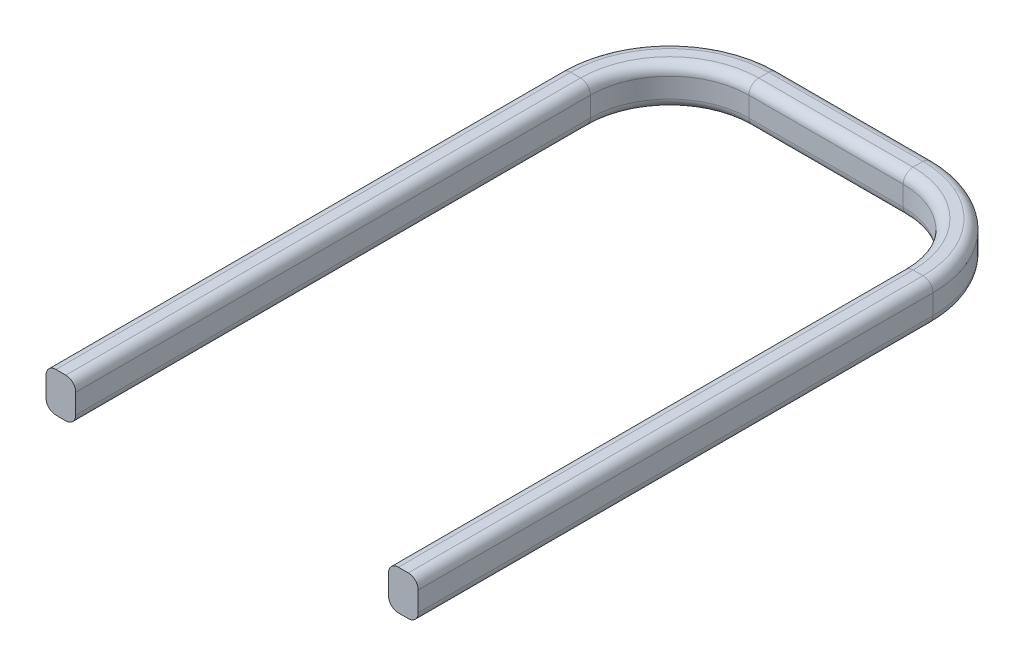
SolidWorks part; units mm, degrees
ref_plane "Front Plane" through (0, 0, 0) normal (0, 0, 1) x (1, 0, 0)
ref_plane "Top Plane" through (0, 0, 0) normal (0, 1, 0) x (1, 0, 0)
ref_plane "Right Plane" through (0, 0, 0) normal (1, 0, 0) x (0, 0, -1)
sketch "Sketch1" plane through (0, 0, 0) normal (0, 1, 0) x (1, 0, 0)
  line L0 (-3.95, 0) -> (-3.95, 13)
  line L1 (-1.95, 15) -> (1.95, 15)
  line L2 (3.95, 13) -> (3.95, 0)
  arc A0 (1.95, 15) -> (3.95, 13) centre (1.95, 13) cw
  arc A1 (-3.95, 13) -> (-1.95, 15) centre (-1.95, 13) cw
  point P2 (0, 0)
  point P5 (0, 15)
  point P11 (-3.95, 15)
  dimension "D3" = 2
  dimension "D1" = 3.95
  dimension "D2" = 15
sketch "Sketch2" plane through (0, 0, 0) normal (0, 0, 1) x (1, 0, 0)
  line L1 (-3.95, 0) -> (-4.7, 0)
  line L2 (-3.95, 0) -> (-3.95, 1)
  line L3 (-3.95, 1) -> (-4.7, 1)
  line L4 (-4.7, 0) -> (-4.7, 1)
  dimension "D1" = 1
  dimension "D2" = 0.75
sweep "Sweep1" add profiles "Sketch2" path "Sketch1"
fillet "Fillet1" radius 0.25 20 edges at (4.7, 0, -6.5) (3.8945, 0, -14.9445) (0, 0, -15.75) (-3.8945, 0, -14.9445) (3.95, 0, -6.5) (3.3642, 0, -14.4142) (0, 0, -15) (-3.3642, 0, -14.4142) (4.7, 1, -6.5) (3.8945, 1, -14.9445) (0, 1, -15.75) (-3.8945, 1, -14.9445) (3.95, 1, -6.5) (3.3642, 1, -14.4142) (0, 1, -15) (-3.3642, 1, -14.4142) (-4.7, 0, -6.5) (-3.95, 0, -6.5) (-4.7, 1, -6.5) (-3.95, 1, -6.5)
